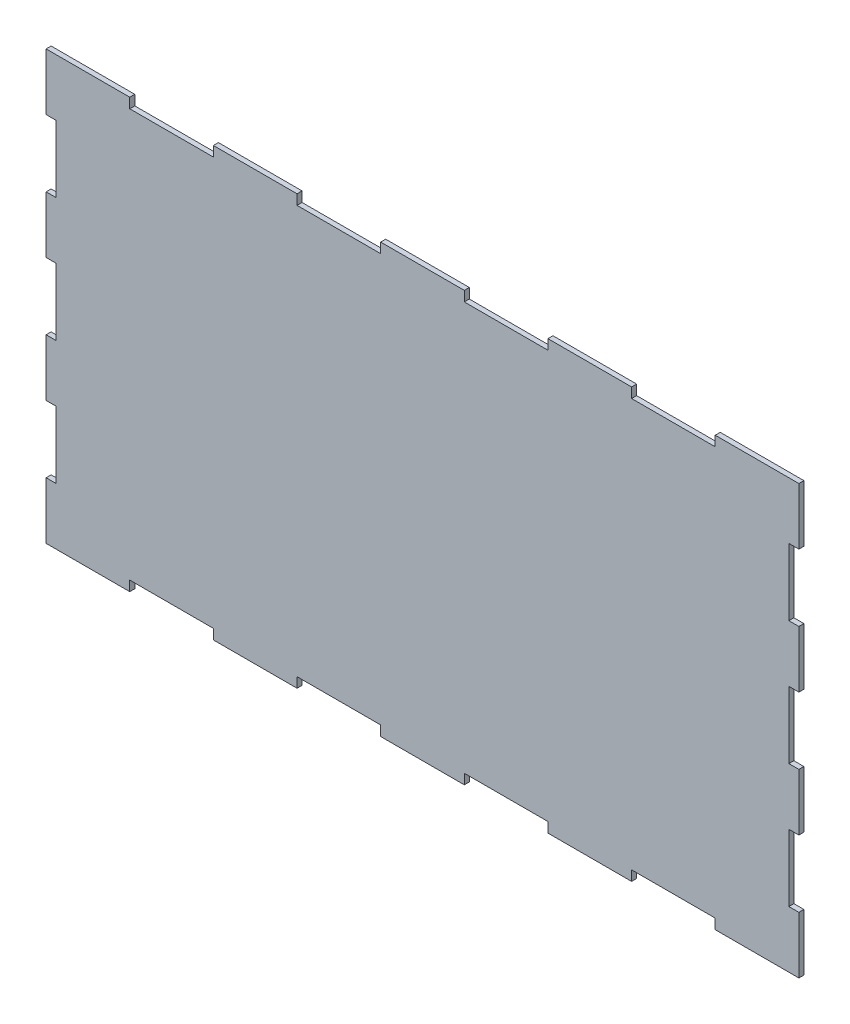
SolidWorks part; units mm, degrees
ref_plane "Спереди" through (0, 0, 0) normal (0, 0, 1) x (1, 0, 0)
ref_plane "Сверху" through (0, 0, 0) normal (0, 1, 0) x (1, 0, 0)
ref_plane "Справа" through (0, 0, 0) normal (1, 0, 0) x (0, 0, -1)
sketch "Эскиз1" plane through (0, 0, 0) normal (0, 0, 1) x (1, 0, 0)
  line L0 (100, 256) -> (150, 256)
  line L1 (0, 0) -> (50, 0)
  line L2 (0, 0) -> (0, 34)
  line L3 (0, 256) -> (50, 256)
  line L4 (450, 0) -> (450, 34)
  line L6 (50, 256) -> (50, 250)
  line L7 (50, 250) -> (100, 250)
  line L8 (100, 256) -> (100, 250)
  line L10 (150, 256) -> (150, 250)
  line L11 (150, 250) -> (200, 250)
  line L12 (200, 256) -> (200, 250)
  line L14 (250, 256) -> (250, 250)
  line L15 (250, 250) -> (300, 250)
  line L16 (300, 256) -> (300, 250)
  line L18 (350, 256) -> (350, 250)
  line L19 (350, 250) -> (400, 250)
  line L20 (400, 256) -> (400, 250)
  line L22 (50, 0) -> (50, 6)
  line L23 (50, 6) -> (100, 6)
  line L24 (100, 0) -> (100, 6)
  line L26 (150, 0) -> (150, 6)
  line L27 (150, 6) -> (200, 6)
  line L28 (200, 0) -> (200, 6)
  line L30 (250, 0) -> (250, 6)
  line L31 (250, 6) -> (300, 6)
  line L32 (300, 0) -> (300, 6)
  line L34 (350, 0) -> (350, 6)
  line L35 (350, 6) -> (400, 6)
  line L36 (400, 0) -> (400, 6)
  line L37 (200, 256) -> (250, 256)
  line L38 (300, 256) -> (350, 256)
  line L39 (400, 256) -> (450, 256)
  line L40 (400, 0) -> (450, 0)
  line L41 (300, 0) -> (350, 0)
  line L42 (200, 0) -> (250, 0)
  line L43 (100, 0) -> (150, 0)
  line L44 (450, 222) -> (450, 256)
  line L45 (450, 222) -> (444, 222)
  line L47 (450, 182) -> (444, 182)
  line L48 (444, 222) -> (444, 182)
  line L49 (450, 148) -> (444, 148)
  line L51 (450, 108) -> (444, 108)
  line L52 (444, 148) -> (444, 108)
  line L53 (450, 74) -> (444, 74)
  line L55 (450, 34) -> (444, 34)
  line L56 (444, 74) -> (444, 34)
  line L57 (0, 222) -> (6, 222)
  line L59 (0, 182) -> (6, 182)
  line L60 (6, 222) -> (6, 182)
  line L61 (0, 148) -> (6, 148)
  line L63 (0, 108) -> (6, 108)
  line L64 (6, 148) -> (6, 108)
  line L65 (0, 74) -> (6, 74)
  line L67 (0, 34) -> (6, 34)
  line L68 (6, 74) -> (6, 34)
  line L69 (450, 148) -> (450, 182)
  line L70 (450, 74) -> (450, 108)
  line L71 (0, 74) -> (0, 108)
  line L72 (0, 148) -> (0, 182)
  line L73 (0, 222) -> (0, 256)
  point P37 (150, 3)
  dimension "D1" = 450
  dimension "D2" = 256
  dimension "D3" = 6
  dimension "D4" = 50
  dimension "D5" = 50
  dimension "D6" = 50
  dimension "D7" = 50
  dimension "D8" = 50
  dimension "D9" = 50
  dimension "D10" = 50
  dimension "D11" = 50
  dimension "D12" = 50
  dimension "D13" = 6
  dimension "D14" = 6
  dimension "D15" = 6
  dimension "D16" = 40
  dimension "D17" = 40
  dimension "D18" = 40
  dimension "D19" = 34
  dimension "D20" = 34
  dimension "D21" = 34
extrude "Бобышка-Вытянуть1" add sketch "Эскиз1" along normal blind 3
